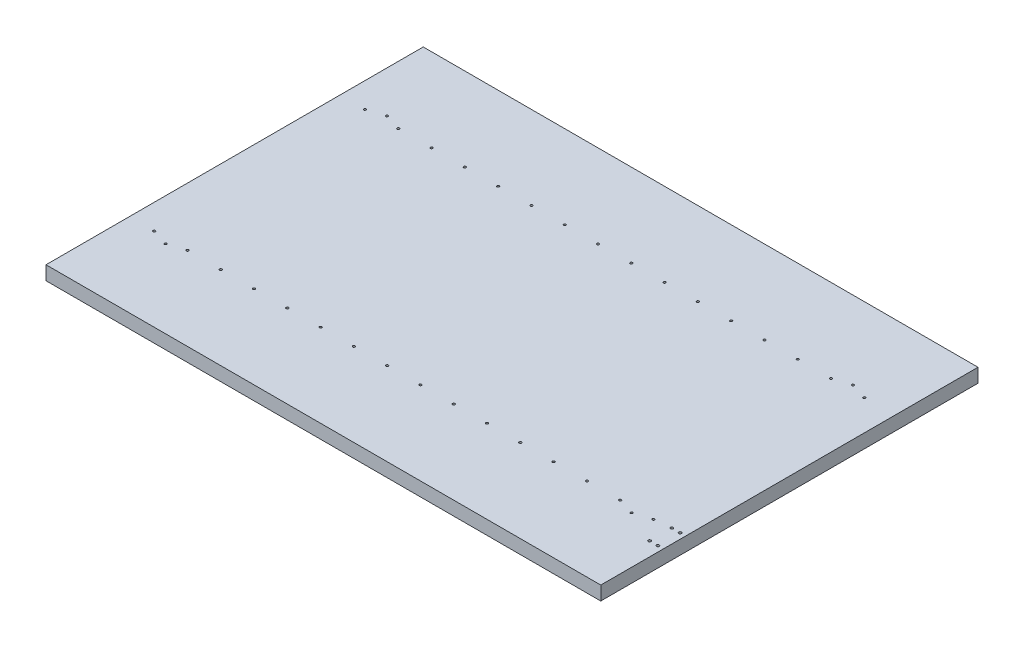
SolidWorks part; units mm, degrees
material "Plain Carbon Steel"
ref_plane "Front Plane" through (0, 0, 0) normal (0, 0, 1) x (1, 0, 0)
ref_plane "Top Plane" through (0, 0, 0) normal (0, 1, 0) x (1, 0, 0)
ref_plane "Right Plane" through (0, 0, 0) normal (1, 0, 0) x (0, 0, -1)
sketch "Sketch1" plane through (0, 0, 0) normal (0, 1, 0) x (1, 0, 0)
  line L1 (500, -340) -> (-500, -340)
  line L2 (500, -340) -> (500, 340)
  line L3 (500, 340) -> (-500, 340)
  line L4 (-500, -340) -> (-500, 340)
  line L5 (500, -340) -> (-500, 340) construction
  line L6 (500, 340) -> (-500, -340) construction
  point P0 (0, 0)
  dimension "D1" = 680
  dimension "D2" = 1000
extrude "Boss-Extrude1" add sketch "Sketch1" along normal mid plane 25
hole_wizard "M5x0.8 Tapped Hole1" positions "Sketch4" profile "Sketch5" tap size "M5x0.8" standard "JIS" end condition through all
sketch "Sketch4" plane through (0, 12.5, 0) normal (0, 1, 0) x (1, 0, 0)
  line L0 (-500, 340) -> (-500, -340) construction
  point P0 (-275, 190)
  point P2 (-215, 190)
  point P4 (-155, 190)
  point P6 (-95, 190)
  point P8 (-35, 190)
  point P10 (25, 190)
  point P12 (85, 190)
  point P14 (145, 190)
  point P16 (205, 190)
  point P18 (265, 190)
  point P20 (325, 190)
  point P22 (385, 190)
  point P24 (445, 190)
  point P53 (-335, 190)
  point P55 (-395, 190)
  point P57 (-455, 190)
  dimension "D1" = 60
  dimension "D2" = 60
  dimension "D3" = 60
  dimension "D4" = 60
  dimension "D5" = 60
  dimension "D6" = 60
  dimension "D7" = 60
  dimension "D8" = 60
  dimension "D9" = 60
  dimension "D10" = 60
  dimension "D11" = 60
  dimension "D12" = 60
  dimension "D13" = 60
  dimension "D14" = 60
  dimension "D15" = 60
  dimension "D16" = 190
  dimension "D17" = 45
sketch "Sketch5" plane through (-275, 12.5, -190) normal (1, 0, 0) x (0, 0, 1)
  line L0 (0, 0) -> (0, 25)
  line L1 (0, 25) -> (2.1, 25)
  line L2 (2.1, 25) -> (2.1, 0)
  line L5 (2.1, 0) -> (0, 0)
  line L11 (0, -6.35) -> (0, 107.95) construction
  dimension "Thru Tap Drill Dia." = 4.2
  dimension "Thru Tap Drill Depth" = 25
cosmetic thread "Hole Thread1" parameters "D2"=5
cosmetic thread "Hole Thread2" parameters "D2"=5
cosmetic thread "Hole Thread3" parameters "D2"=5
cosmetic thread "Hole Thread4" parameters "D2"=5
cosmetic thread "Hole Thread5" parameters "D2"=5
cosmetic thread "Hole Thread6" parameters "D2"=5
cosmetic thread "Hole Thread7" parameters "D2"=5
cosmetic thread "Hole Thread8" parameters "D2"=5
cosmetic thread "Hole Thread9" parameters "D2"=5
cosmetic thread "Hole Thread10" parameters "D2"=5
cosmetic thread "Hole Thread11" parameters "D2"=5
cosmetic thread "Hole Thread12" parameters "D2"=5
cosmetic thread "Hole Thread13" parameters "D2"=5
cosmetic thread "Hole Thread27" parameters "D2"=5
cosmetic thread "Hole Thread28" parameters "D2"=5
cosmetic thread "Hole Thread29" parameters "D2"=5
mirror "Mirror1" about plane through (0, 0, 0) normal (0, 0, 1) of "M5x0.8 Tapped Hole1"
cosmetic thread "Hole Thread14" parameters "D2"=5
cosmetic thread "Hole Thread15" parameters "D2"=5
cosmetic thread "Hole Thread16" parameters "D2"=5
cosmetic thread "Hole Thread17" parameters "D2"=5
cosmetic thread "Hole Thread18" parameters "D2"=5
cosmetic thread "Hole Thread19" parameters "D2"=5
cosmetic thread "Hole Thread20" parameters "D2"=5
cosmetic thread "Hole Thread21" parameters "D2"=5
cosmetic thread "Hole Thread22" parameters "D2"=5
cosmetic thread "Hole Thread23" parameters "D2"=5
cosmetic thread "Hole Thread24" parameters "D2"=5
cosmetic thread "Hole Thread25" parameters "D2"=5
cosmetic thread "Hole Thread26" parameters "D2"=5
cosmetic thread "Hole Thread30" parameters "D2"=5
cosmetic thread "Hole Thread31" parameters "D2"=5
cosmetic thread "Hole Thread32" parameters "D2"=5
hole_wizard "M6 Tapped Hole1" positions "Sketch9" profile "Sketch10" tap size "M6" standard "ISO" end condition through all
sketch "Sketch9" plane through (0, 12.5, 0) normal (0, 1, 0) x (1, 0, 0)
  line L0 (500, -340) -> (500, 340) construction
  circle A0 centre (445, -190) radius 2.1 construction
  point P0 (475, -187)
  point P2 (490, -187)
  point P4 (490, -227)
  point P6 (475, -227)
  dimension "D1" = 15
  dimension "D2" = 40
  dimension "D3" = 10
  dimension "D4" = 37
sketch "Sketch10" plane through (475, 12.5, 187) normal (1, 0, 0) x (0, 0, 1)
  line L0 (0, 0) -> (0, 25)
  line L1 (0, 25) -> (2.5, 25)
  line L2 (2.5, 25) -> (2.5, 0)
  line L5 (2.5, 0) -> (0, 0)
  line L11 (0, -6.35) -> (0, 107.95) construction
  dimension "Thru Tap Drill Dia." = 5
  dimension "Thru Tap Drill Depth" = 25
hole_wizard "Ø4.0mm Dowel Hole1" positions "Sketch11" profile "Sketch12" hole size "Ø4.0" standard "JIS"
sketch "Sketch11" plane through (0, 12.5, 0) normal (0, 1, 0) x (1, 0, 0)
  circle A0 centre (445, -190) radius 2.1 construction
  circle A1 centre (-455, -190) radius 2.1 construction
  point P0 (415, -199.5)
  point P2 (-425, -199.5)
  dimension "D1" = 9.5
  dimension "D3" = 30
  dimension "D2" = 840
  dimension "D4" = 30
sketch "Sketch12" plane through (415, 12.5, 199.5) normal (1, 0, 0) x (0, 0, 1)
  line L0 (0, 0) -> (0, 21.2017)
  line L1 (0, 21.2017) -> (2, 20)
  line L2 (2, 20) -> (2, 0)
  line L5 (2, 0) -> (0, 0)
  line L10 (0, 21.2017) -> (-2, 20) construction
  line L11 (0, -6.35) -> (0, 107.95) construction
  dimension "Hole Dia." = 4
  dimension "Hole Depth" = 20
  dimension "Drill Angle" = 118
mirror "Mirror2" about plane through (0, 0, 0) normal (0, 0, 1) of "Ø4.0mm Dowel Hole1"
equation "\"D5@Sketch4\"=\"D1@Sketch4\""
equation "\"D2@Sketch4\"=\"D1@Sketch4\""
equation "\"D3@Sketch4\"=\"D1@Sketch4\""
equation "\"D4@Sketch4\"=\"D1@Sketch4\""
equation "\"D6@Sketch4\"=\"D1@Sketch4\""
equation "\"D7@Sketch4\"=\"D1@Sketch4\""
equation "\"D8@Sketch4\"=\"D1@Sketch4\""
equation "\"D9@Sketch4\"=\"D1@Sketch4\""
equation "\"D10@Sketch4\"=\"D1@Sketch4\""
equation "\"D11@Sketch4\"=\"D1@Sketch4\""
equation "\"D12@Sketch4\"=\"D1@Sketch4\""
equation "\"D13@Sketch4\"=\"D1@Sketch4\""
equation "\"D15@Sketch4\"=\"D1@Sketch4\""
equation "\"D14@Sketch4\"=\"D1@Sketch4\""
